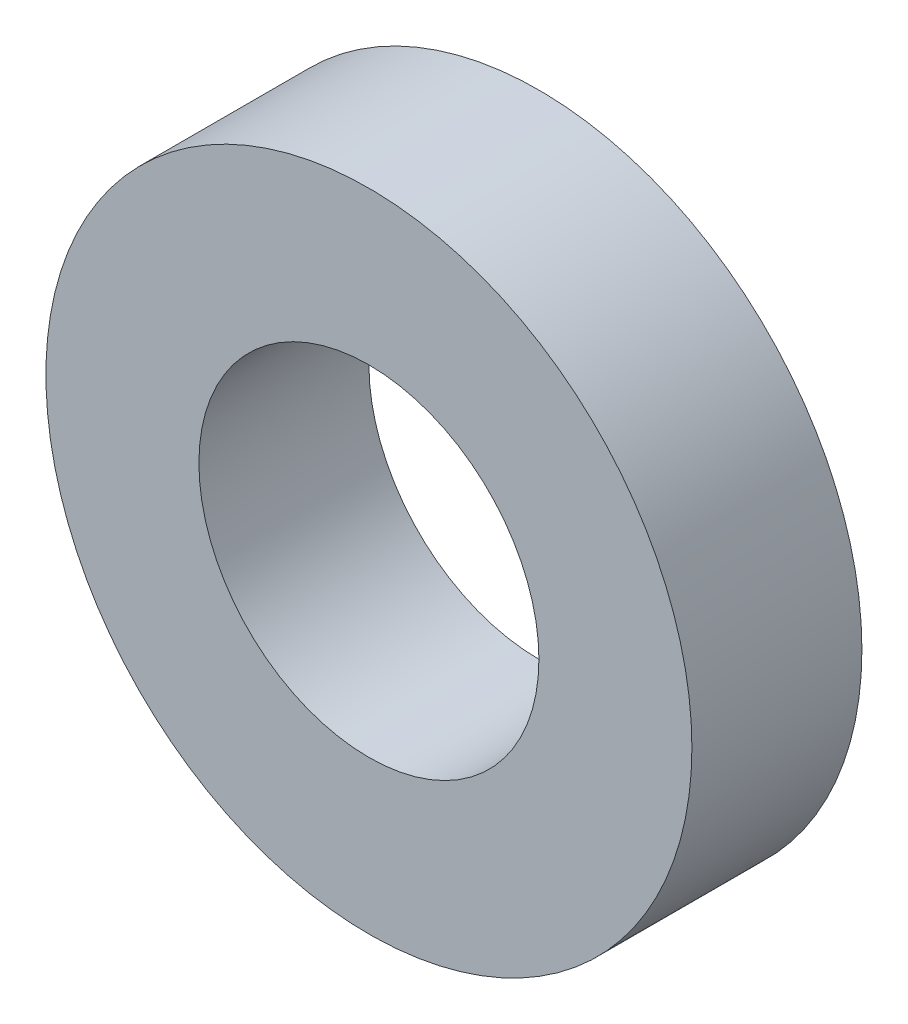
SolidWorks part; units mm, degrees
material "1060 Alloy"
ref_plane "Front Plane" through (0, 0, 0) normal (0, 0, 1) x (1, 0, 0)
ref_plane "Top Plane" through (0, 0, 0) normal (0, 1, 0) x (1, 0, 0)
ref_plane "Right Plane" through (0, 0, 0) normal (1, 0, 0) x (0, 0, -1)
sketch "Sketch1" plane through (0, 0, 0) normal (0, 0, 1) x (1, 0, 0)
  circle A0 centre (0, 0) radius 9.5
extrude "Boss-Extrude1" add sketch "Sketch1" along normal blind 5
sketch "Sketch2" plane through (0, 0, 5) normal (0, 0, 1) x (1, 0, 0)
  circle A0 centre (0, 0) radius 5
extrude "Cut-Extrude1" cut sketch "Sketch2" against normal blind 5
